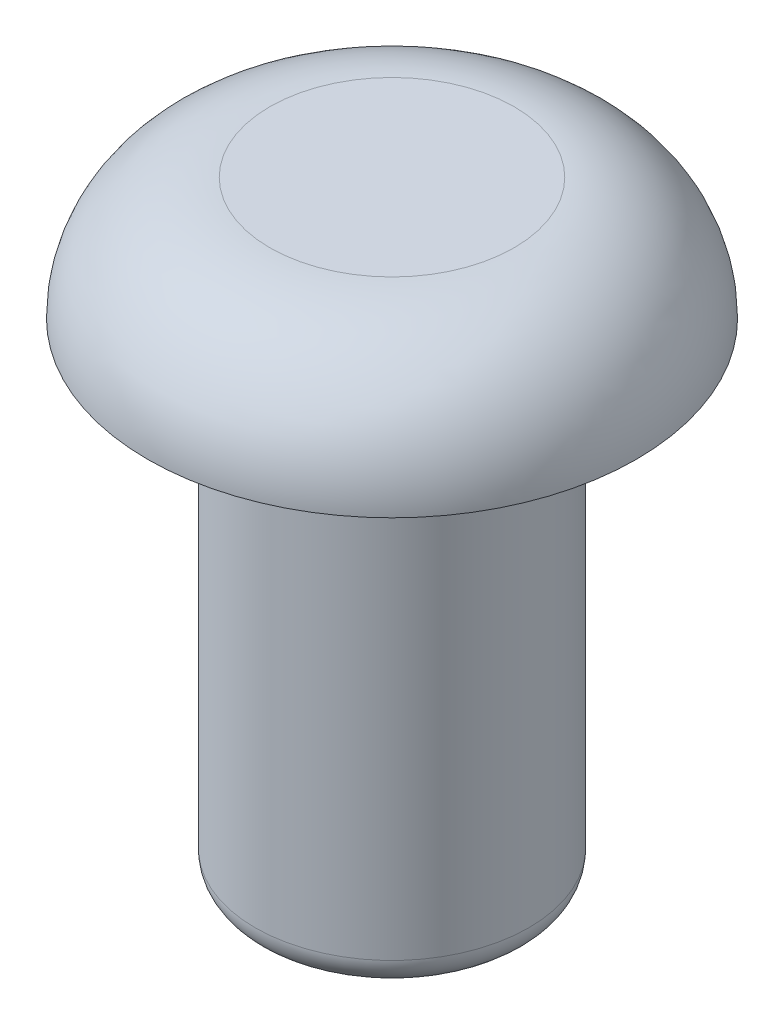
SolidWorks part; units mm, degrees
material "AISI 316 Annealed Stainless Steel Bar (SS)"
ref_plane "Front Plane" through (0, 0, 0) normal (0, 0, 1) x (1, 0, 0)
ref_plane "Top Plane" through (0, 0, 0) normal (0, 1, 0) x (1, 0, 0)
ref_plane "Right Plane" through (0, 0, 0) normal (1, 0, 0) x (0, 0, -1)
sketch "Sketch1" plane through (0, 0, 0) normal (1, 0, 0) x (0, 0, -1)
  line L0 (0, 0) -> (0, 4.7969) construction
  line L1 (0, 0) -> (1.778, 0)
  line L2 (1.778, 0) -> (1.778, 6.35)
  line L3 (1.778, 6.35) -> (3.175, 6.35)
  line L4 (0, 7.9375) -> (1.5875, 7.9375)
  line L5 (0, 7.9375) -> (0, 0)
  arc A0 (1.5875, 7.9375) -> (3.175, 6.35) centre (1.5875, 6.35) cw
  dimension "D1" = 3.556
  dimension "D2" = 6.35
  dimension "D3" = 6.35
  dimension "D4" = 3.175
  dimension "D5" = 1.5875
revolve "Revolve1" add sketch "Sketch1" angle 360 about L0
fillet "Fillet1" radius 0.381 1 edges at (0, 0, -1.778)
